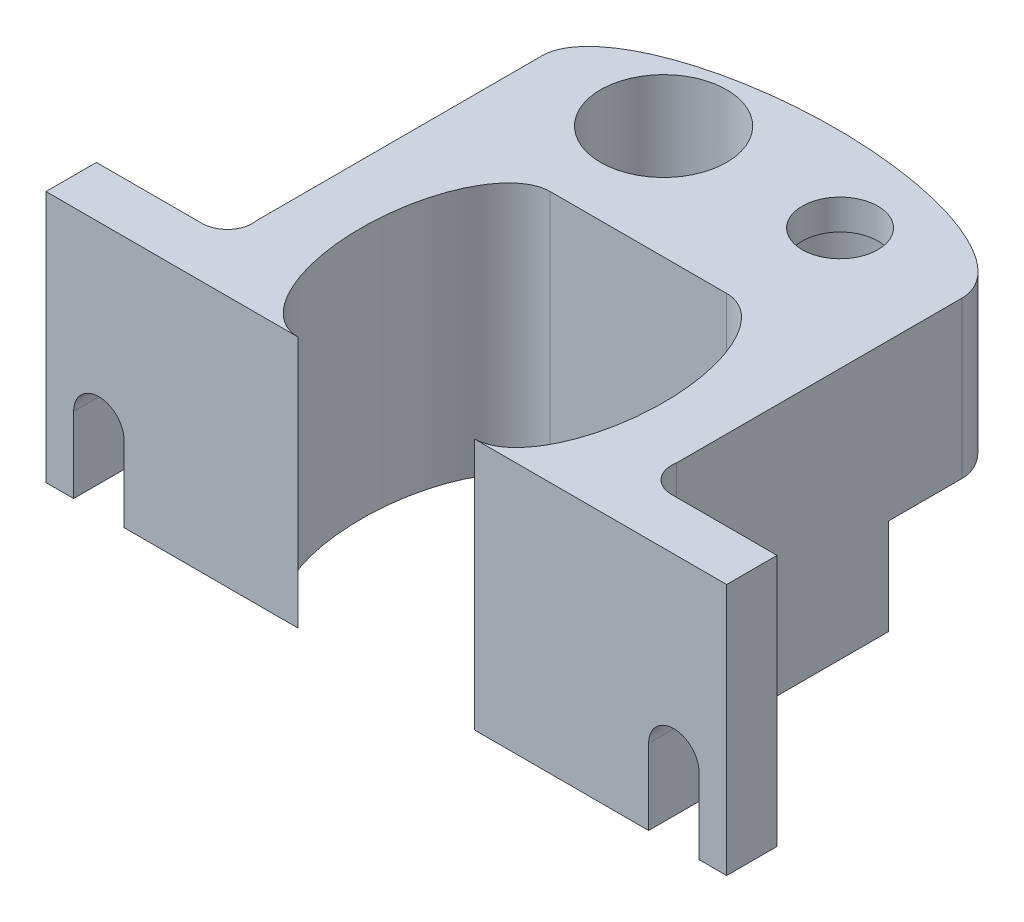
SolidWorks part; units mm, degrees
ref_plane "Front Plane" through (0, 0, 0) normal (0, 0, 1) x (1, 0, 0)
ref_plane "Top Plane" through (0, 0, 0) normal (0, 1, 0) x (1, 0, 0)
ref_plane "Right Plane" through (0, 0, 0) normal (1, 0, 0) x (0, 0, -1)
sketch "Sketch1" plane through (0, 0, 0) normal (0, 1, 0) x (1, 0, 0)
  line L0 (-3.5, -5) -> (-13.5, -5)
  line L1 (-3.5, -5) -> (3.5, -5) construction
  line L2 (-3.5, -5) -> (-3.5, 5) construction
  line L3 (-3.5, 5) -> (3.5, 5)
  line L4 (3.5, -5) -> (3.5, 5) construction
  line L5 (-3.5, -5) -> (3.5, 5) construction
  line L6 (-3.5, 5) -> (3.5, -5) construction
  line L7 (-13.5, -5) -> (-13.5, -3)
  line L8 (-13.5, -3) -> (-9.3079, -3)
  line L9 (3.5, -5) -> (13.5, -5)
  line L10 (13.5, -5) -> (13.5, -3)
  line L11 (13.5, -3) -> (9.3112, -3)
  line L12 (-8.3257, -1.8121) -> (-8.3257, 6.6)
  line L13 (-8.3257, 6.6) -> (8.3291, 6.6)
  line L14 (8.3291, -1.8119) -> (8.3291, 6.6)
  arc A0 (-9.3079, -3) -> (-8.3257, -1.8121) centre (-9.3079, -2) ccw
  arc A1 (9.3112, -3) -> (8.3291, -1.8119) centre (9.3112, -2) cw
  ellipse E0 centre (-3.5, 0) end of major axis (-3.5, 5) minor radius 2.4998 (-3.5, 5) -> (-3.5, -5) ccw
  ellipse E1 centre (3.5, 0) end of major axis (3.5, 5) minor radius 2.4987 (3.5, -5) -> (3.5, 5) ccw
  ellipse E3 centre (3.5, 0) end of major axis (3.5, 6.9986) minor radius 4.9996 (0.0018, 5) -> (-0.0012, 4.9959) ccw
  ellipse E4 centre (-3.5, 0) end of major axis (-3.5, 6.9986) minor radius 4.996 (-0.0012, 4.9959) -> (-0.0042, 5) ccw
  ellipse E5 centre (3.5, 0) end of major axis (3.5, 6.9986) minor radius 4.9996 (-0.0012, -4.9959) -> (0.0018, -5) ccw
  ellipse E7 centre (-3.5, 0) end of major axis (-3.5, 6.9986) minor radius 4.996 (-0.0042, -5) -> (-0.0012, -4.9959) ccw
  point P0 (0, 0)
  dimension "D6" = 1
  dimension "D7" = 1
  dimension "D1" = 7
  dimension "D2" = 10
  dimension "D3" = 10
  dimension "D4" = 2
  dimension "D5" = 10
  dimension "D9" = 1.6
extrude "Boss-Extrude1" add sketch "Sketch1" along normal blind 10
sketch "Sketch2" plane through (0, 0, 3) normal (0, 0, -1) x (-1, 0, 0)
  line L0 (-13.5, 10) -> (-9.3112, 0) construction
  line L1 (-13.5, 0) -> (-9.3112, 10) construction
  line L2 (13.5, 10) -> (9.3079, 0) construction
  line L3 (13.5, 0) -> (9.3079, 0) construction
  line L4 (13.5, 0) -> (9.3079, 10) construction
  line L5 (-11.4056, 5) -> (-11.4056, -2.9743) construction
  line L6 (-11.4056, -0.7517) -> (-11.4056, 3) construction
  line L7 (10.4039, 0) -> (12.4039, 0)
  line L9 (-13.5, 0) -> (-9.3112, 0) construction
  line L10 (11.4039, 5) -> (11.4039, -2.9743) construction
  line L11 (11.4039, -1.6148) -> (11.4039, 3) construction
  line L12 (-12.4056, 0) -> (-10.4056, 0)
  line L14 (-12.4056, 3) -> (-12.4056, 0)
  line L15 (-10.4056, 3) -> (-10.4056, 0)
  line L16 (10.4039, 3) -> (10.4039, 0)
  line L17 (12.4039, 3) -> (12.4039, 0)
  arc A1 (-10.4056, 3) -> (-12.4056, 3) centre (-11.4056, 3) ccw
  arc A3 (12.4039, 3) -> (10.4039, 3) centre (11.4039, 3) ccw
  point P20 (-11.4056, 1.1242)
  point P32 (11.4039, 0.6926)
  dimension "D1" = 1
  dimension "D2" = 3
  dimension "D3" = 1
  dimension "D4" = 3
extrude "Cut-Extrude1" cut sketch "Sketch2" against normal blind 10
sketch "Sketch3" plane through (0, 10, 0) normal (0, 1, 0) x (1, 0, 0)
  line L0 (-3.5, 5) -> (-3.5, 12.9854) construction
  line L1 (3.5, 5) -> (3.5, 12.9854) construction
  line L2 (-8.3257, 6.6) -> (8.3291, 6.6)
  line L3 (-8.496, 9.4986) -> (3.5, 9.4986) construction
  line L4 (8.3291, 6.6) -> (8.3291, 9.4986)
  line L5 (-8.3257, 6.6) -> (-8.3257, 9.5941)
  circle A0 centre (-3.5, 9.4986) radius 2.5
  circle A1 centre (3.5, 9.4986) radius 2.5 construction
  circle A2 centre (3.5, 9.4986) radius 1.5
  circle A3 centre (0, 0) radius 13.8 construction
  circle A4 centre (-3.5, 9.4986) radius 2.85 construction
  circle A5 centre (3.5, 9.4986) radius 2.85 construction
  ellipse E4 centre (0, 9.4986) end of major axis (8.3291, 9.4986) minor radius 3.3362 (8.3291, 9.4986) -> (-8.3257, 9.5941) ccw
  ellipse E5 centre (-3.5, 0) end of major axis (-3.5, 7) minor radius 5 (-3.4367, 6.9994) -> (-3.5633, 6.9994) ccw
  dimension "D1" = 5
  dimension "D2" = 3
  dimension "D3" = 27.6
  dimension "D4" = 5.7
  dimension "D5" = 5.7
extrude "Boss-Extrude2" add sketch "Sketch3" against normal blind 1.2
sketch "Sketch4" plane through (0, 8.8, 0) normal (0, -1, 0) x (1, 0, 0)
  line L0 (-8.3257, -6.6) -> (8.3291, -6.6)
  line L1 (8.3291, -6.6) -> (8.3291, -9.4986)
  line L2 (-8.3257, -6.6) -> (-8.3257, -9.5941)
  line L3 (-3.5, -9.4986) -> (3.5, -9.4986) construction
  circle A0 centre (-3.5, -9.4986) radius 2.5
  circle A1 centre (3.5, -9.4986) radius 2.5
  ellipse E1 centre (0, -9.4986) end of major axis (8.3291, -9.4986) minor radius 3.3362 (-8.3257, -9.4032) -> (8.3291, -9.4986) ccw
  dimension "D1" = 5
  dimension "D2" = 5
extrude "Boss-Extrude3" add sketch "Sketch4" along normal blind 5
